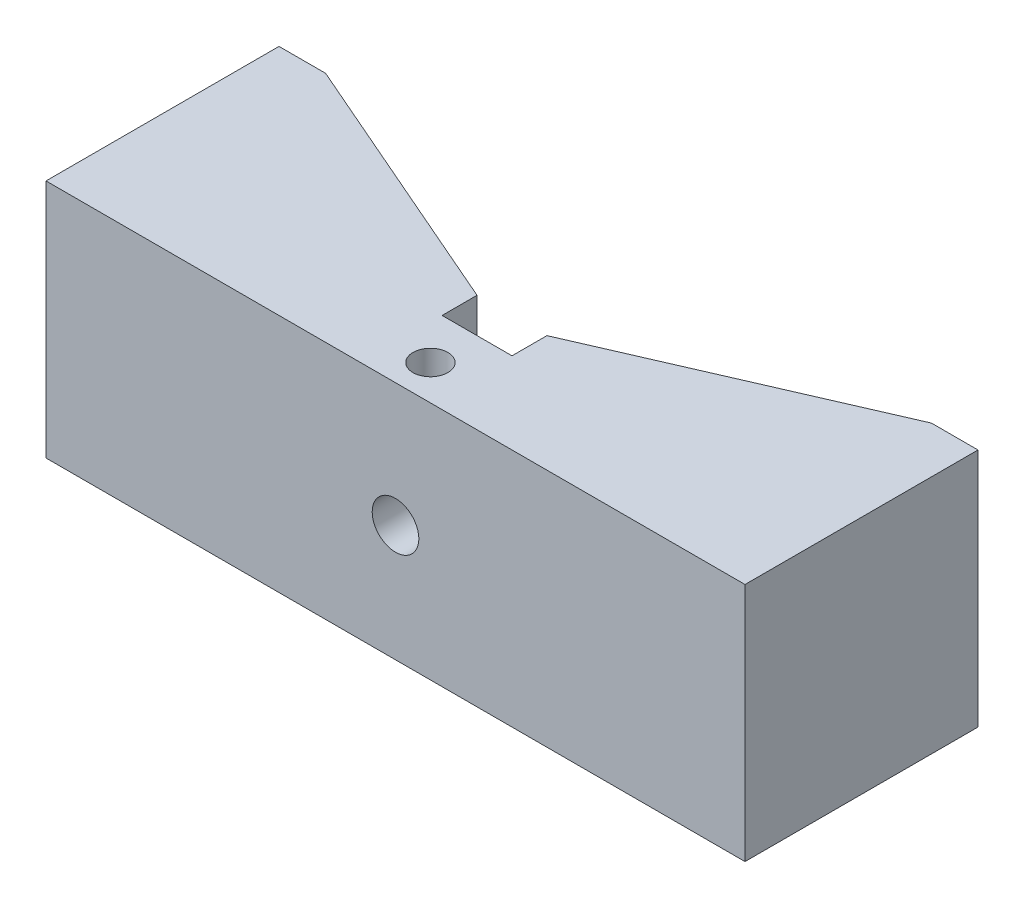
SolidWorks part; units mm, degrees
ref_plane "Front" through (0, 0, 0) normal (0, 0, 1) x (1, 0, 0)
ref_plane "Top" through (0, 0, 0) normal (0, 1, 0) x (1, 0, 0)
ref_plane "Right" through (0, 0, 0) normal (1, 0, 0) x (0, 0, -1)
sketch "Sketch1" plane through (0, 0, 0) normal (0, 1, 0) x (1, 0, 0)
  line L0 (0, 12.7) -> (0, -12.7) construction
  line L1 (38.1, -12.7) -> (-38.1, -12.7)
  line L2 (38.1, -12.7) -> (38.1, 12.7)
  line L3 (38.1, 12.7) -> (33.02, 12.7)
  line L4 (-38.1, -12.7) -> (-38.1, 12.7)
  line L5 (38.1, -12.7) -> (3.81, -1.27) construction
  line L6 (38.1, 12.7) -> (16.3286, 5.4429) construction
  line L7 (-38.1, 0) -> (-3.81, 0) construction
  line L8 (-33.02, 12.7) -> (-3.81, 0)
  line L9 (33.02, 12.7) -> (3.81, 0)
  line L11 (-33.02, 12.7) -> (-38.1, 12.7)
  line L12 (-3.81, 0) -> (-3.81, -3.81)
  line L13 (-3.81, -3.81) -> (3.81, -3.81)
  line L14 (3.81, -3.81) -> (3.81, 0)
  line L15 (-16.3286, 5.4429) -> (-38.1, 12.7) construction
  line L16 (3.81, 0) -> (38.1, 0) construction
  line L17 (-3.81, -1.27) -> (-38.1, -12.7) construction
  point P0 (0, 0)
  dimension "D1" = 25.4
  dimension "D2" = 76.2
  dimension "D3" = 5.08
  dimension "D4" = 3.81
  dimension "D5" = 7.62
  dimension "D6" = 3.81
extrude "Boss-Extrude1" add sketch "Sketch1" along normal blind 26.162
sketch "Sketch2" plane through (0, 0, 3.81) normal (0, 0, -1) x (-1, 0, 0)
  line L0 (0, 0) -> (0, 26.162) construction
  line L1 (-3.81, 0) -> (3.81, 0) construction
  line L2 (-3.81, 26.162) -> (3.81, 26.162) construction
  circle A0 centre (0, 12.7) radius 2.54
  dimension "D1" = 5.08
  dimension "D2" = 12.7
sketch "Sketch3" plane through (0, 26.162, 0) normal (0, 1, 0) x (1, 0, 0)
  line L0 (0, -3.81) -> (0, -12.7) construction
  line L1 (3.81, -3.81) -> (-3.81, -3.81) construction
  line L2 (-38.1, -12.7) -> (38.1, -12.7) construction
  circle A0 centre (0, -8.89) radius 1.905
  dimension "D1" = 3.81
  dimension "D2" = 3.81
extrude "Cut-Extrude2" cut sketch "Sketch3" against normal blind 5.08 contours A0
extrude "Cut-Extrude3" cut sketch "Sketch2" against normal through all
